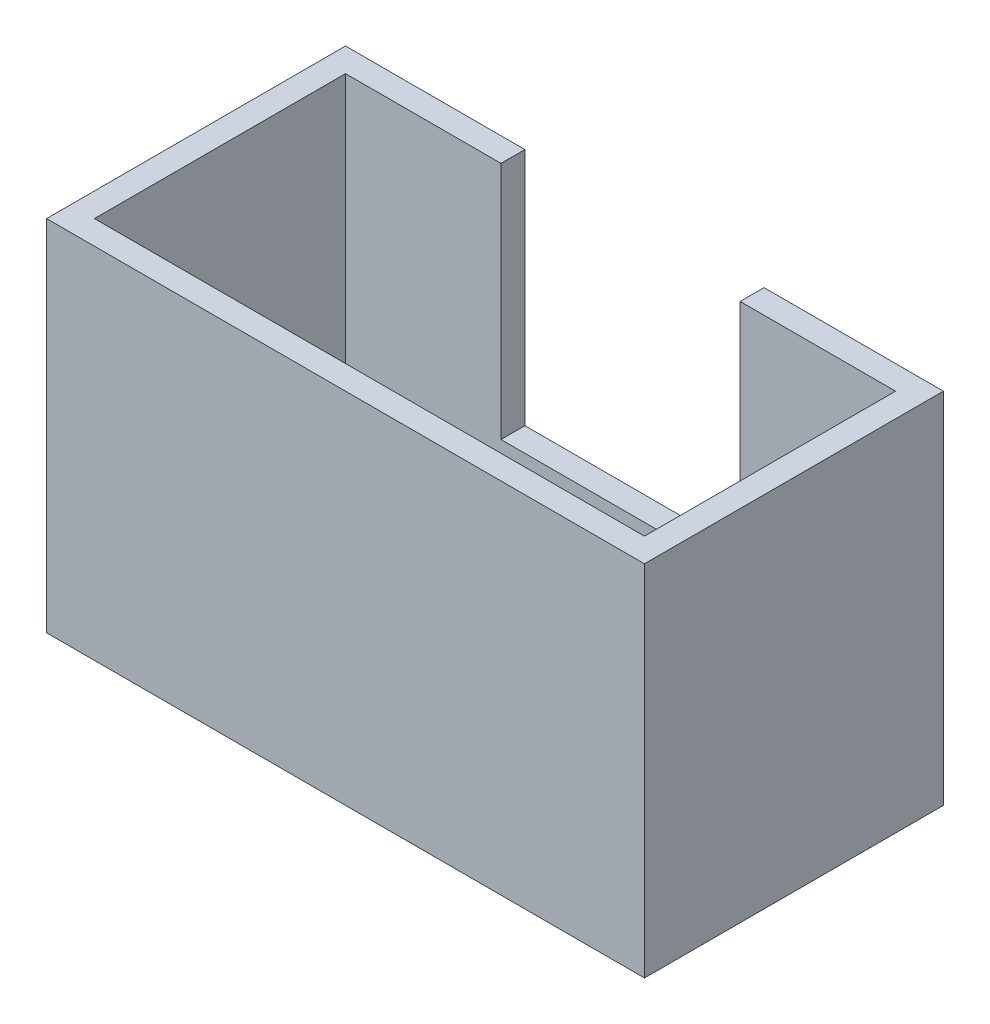
SolidWorks part; units mm, degrees
ref_plane "前视基准面" through (0, 0, 0) normal (0, 0, 1) x (1, 0, 0)
ref_plane "上视基准面" through (0, 0, 0) normal (0, 1, 0) x (1, 0, 0)
ref_plane "右视基准面" through (0, 0, 0) normal (1, 0, 0) x (0, 0, -1)
sketch "草图1" plane through (0, 0, 0) normal (0, 0, 1) x (1, 0, 0)
  line L1 (0, 0) -> (10, 0)
  line L2 (0, 0) -> (0, 6)
  line L3 (0, 6) -> (10, 6)
  line L4 (10, 0) -> (10, 6)
  dimension "D1" = 10
  dimension "D2" = 6
extrude "凸台-拉伸1" add sketch "草图1" along normal blind 5
shell "抽壳1" thickness 0.4
sketch "草图2" plane through (0, 0, 0) normal (0, 0, -1) x (-1, 0, 0)
  line L0 (-5, 6) -> (-5, 0) construction
  line L1 (-10, 6) -> (0, 6) construction
  line L2 (0, 0) -> (-10, 0) construction
  line L3 (-7, 6) -> (-7, 2)
  line L4 (-7, 2) -> (-3, 2)
  line L5 (-3, 6) -> (-3, 2)
  line L6 (-7, 6) -> (-3, 6)
  point P10 (-5, 2)
  dimension "D1" = 4
  dimension "D2" = 2
extrude "切除-拉伸1" cut sketch "草图2" against normal up to next
